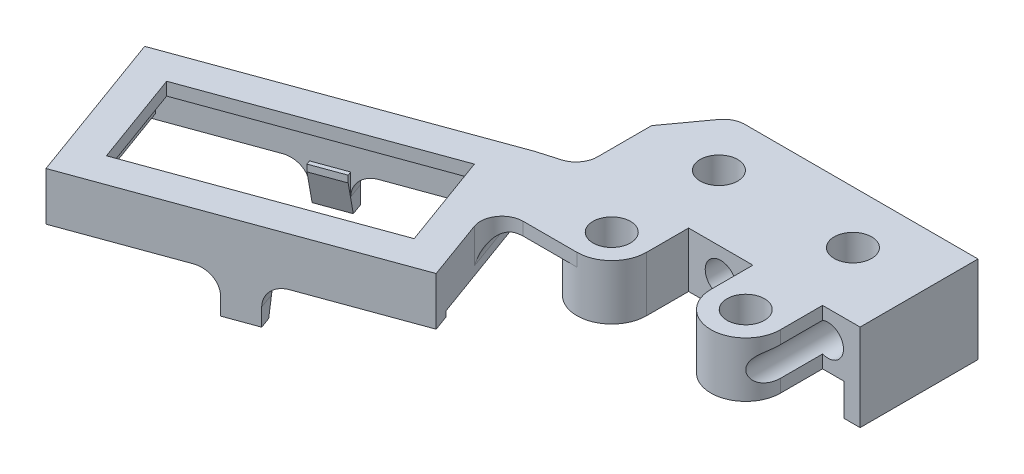
SolidWorks part; units mm, degrees
ref_plane "Front Plane" through (0, 0, 0) normal (0, 0, 1) x (1, 0, 0)
ref_plane "Top Plane" through (0, 0, 0) normal (0, 1, 0) x (1, 0, 0)
ref_plane "Right Plane" through (0, 0, 0) normal (1, 0, 0) x (0, 0, -1)
sketch "Sketch1" plane through (0, 0, 0) normal (0, 1, 0) x (1, 0, 0)
  line L5 (0, 0) -> (16.0528, 0) construction
  line L6 (0, 0) -> (0, -25.9338) construction
  line L7 (-6.25, 5) -> (-6.25, -5) construction
  line L8 (-6.25, 0) -> (0, 0) construction
  line L10 (-13, 9.92) -> (13, 9.92)
  line L11 (-13, 9.92) -> (-13, -9.92)
  line L12 (-13, -9.92) -> (13, -9.92)
  line L13 (13, 9.92) -> (13, -9.92)
  line L14 (-13, 9.92) -> (13, -9.92) construction
  line L15 (-13, -9.92) -> (13, 9.92) construction
  circle A7 centre (-6.25, 5) radius 1.75
  circle A8 centre (-6.25, -5) radius 1.75
  circle A9 centre (6.25, -5) radius 1.75
  circle A10 centre (6.25, 5) radius 1.75
  dimension "D3" = 3.5
  dimension "D4" = 12.5
  dimension "D5" = 10
  dimension "D7" = 26
  dimension "D8" = 4.92
extrude "Boss-Extrude1" add sketch "Sketch1" along normal blind 5.13 contours L13 L10 L11 L12 A9 A8 A7 A10
sketch "Sketch2" plane through (0, 0, 9.92) normal (0, 0, 1) x (1, 0, 0)
  line L0 (-13, 2.565) -> (13, 2.565) construction
  line L1 (-13, 5.13) -> (-13, 0) construction
  line L2 (13, 5.13) -> (13, 0) construction
  line L3 (0, 0) -> (0, 5.13) construction
  line L4 (-13, 5.13) -> (13, 5.13) construction
  circle A0 centre (0, 2.565) radius 1.45
  circle A1 centre (-10, 2.565) radius 1.45
  circle A2 centre (10, 2.565) radius 1.45
  dimension "D1" = 2.9
  dimension "D2" = 10
extrude "Cut-Extrude1" cut sketch "Sketch2" against normal up to next
sketch "Sketch3" plane through (0, 0, 0) normal (0, -1, 0) x (1, 0, 0)
  line L6 (-11.035, -9.92) -> (11.035, -9.92)
  line L7 (0, -9.92) -> (0, 3.71) construction
  line L8 (-13, -9.92) -> (13, -9.92) construction
  line L9 (-11.63, 3.71) -> (11.63, 3.71)
  line L10 (0, 3.71) -> (0, -9.92) construction
  line L11 (11.035, -9.92) -> (11.63, 3.71)
  line L12 (-11.035, -9.92) -> (-11.63, 3.71)
  line L13 (-10.92, 6.04) -> (10.92, 6.04)
  line L14 (0, 6.04) -> (0, -9.92) construction
  line L15 (-7.625, 12.72) -> (7.625, 12.72)
  line L16 (0, 12.72) -> (0, -9.92) construction
  line L17 (-7.625, 12.72) -> (-10.92, 6.04)
  line L18 (10.92, 6.04) -> (7.625, 12.72)
  line L19 (-9.0061, 9.92) -> (9.0061, 9.92)
  line L20 (-13, 9.92) -> (13, 9.92) construction
  line L22 (-13, 9.92) -> (13, 9.92)
  line L23 (-13, 9.92) -> (-13, -9.92)
  line L24 (-13, -9.92) -> (13, -9.92)
  line L25 (13, 9.92) -> (13, -9.92)
  spline S0 degree 2 poles (-11.63, 3.71) (-10.5122, 4.4663) (-10.92, 6.04) knots 0 0 0 1 1 1
  spline S1 degree 2 poles (11.63, 3.71) (10.5122, 4.4663) (10.92, 6.04) knots 0 0 0 1 1 1
  line M4 (13, -9.92) -> (13, 9.92)
  line M5 (13, 9.92) -> (-13, 9.92)
  line M6 (-13, 9.92) -> (-13, -9.92)
  line M7 (-13, -9.92) -> (13, -9.92)
  dimension "D8" = 22.07
  dimension "D9" = 23.26
  dimension "D11" = 13.63
  dimension "D12" = 21.84
  dimension "D14" = 2.33
  dimension "D15" = 15.25
  dimension "D17" = 6.68
extrude "Boss-Extrude2" add sketch "Sketch3" along normal blind 3 contours L12 S0 L17 M5 M6 M7 | S1 L11 L18 M7 M4 M5
sketch "Sketch4" plane through (0, -3, 0) normal (0, -1, 0) x (1, 0, 0)
  line L0 (-13, 1.08) -> (13, 1.08)
  line L1 (-13, 9.92) -> (-13, -9.92) construction
  line L2 (13, -9.92) -> (13, 9.92) construction
  line L3 (-9.5, 5) -> (-9.5, 1.08)
  line L4 (-11.035, -9.92) -> (11.035, -9.92) construction
  line L5 (-3, 5) -> (-3, 1.08)
  line L6 (3, 5) -> (3, 1.08)
  line L7 (9.5, 5) -> (9.5, 1.08)
  line L8 (-13, 1.08) -> (-13, 9.92)
  line L9 (-13, 9.92) -> (13, 9.92)
  line L10 (13, 9.92) -> (13, 1.08)
  circle A0 centre (-6.25, 5) radius 3.25
  circle A1 centre (-6.25, 5) radius 1.75 construction
  circle A2 centre (6.25, 5) radius 3.25
  spline M1 degree 2 poles (10.92, 6.04) (10.5122, 4.4663) (11.63, 3.71) knots 0 0 0 1 1 1
  line M2 (11.63, 3.71) -> (11.035, -9.92)
  line M4 (13, -9.92) -> (13, 9.92)
  line M5 (13, 9.92) -> (9.0061, 9.92)
  line M6 (9.0061, 9.92) -> (10.92, 6.04)
  dimension "D1" = 11
  dimension "D2" = 1.5
extrude "Cut-Extrude2" cut sketch "Sketch4" against normal up to next contours A2 L7 L0 L9 L8 L3 A0 L5 L6 M2 M1 M6 | L0 M2 M4 M5 M6 M1
sketch "Sketch5" plane through (0, 5.13, 0) normal (0, 1, 0) x (1, 0, 0)
  line L0 (-18.8665, -2.6039) -> (-10.3647, 9.0978) construction
  line L1 (-18.8665, -2.6039) -> (-10.3647, 9.0978)
  line L2 (-8.7467, 9.9222) -> (-13, 9.92)
  line L3 (-13, 9.92) -> (-13, 5.4706)
  line L4 (-13, 9.92) -> (-13, -1.08) construction
  arc A0 (-8.7467, 9.9222) -> (-10.3647, 9.0978) centre (-8.7467, 7.9222) ccw construction
  arc A1 (-8.7467, 9.9222) -> (-10.3647, 9.0978) centre (-8.7467, 7.9222) ccw
  line M3 (13, 9.92) -> (-13, 9.92)
  line M4 (-13, 9.92) -> (-13, -1.08)
extrude "Cut-Extrude3" cut sketch "Sketch5" against normal up to next contours A1 L1 M3 M4
sketch "Sketch6" plane through (0, 5.13, 0) normal (0, -1, 0) x (1, 0, 0)
  line L0 (-37.7857, 26.2448) -> (-11.0984, 16.5315)
  line L1 (-41.1302, 12.6701) -> (-17.262, 3.9828)
  line L2 (-41.1302, 12.6701) -> (-36.8892, 24.3223)
  line L3 (-36.8892, 24.3223) -> (-13.021, 15.6349)
  line L4 (-17.262, 3.9828) -> (-13.021, 15.6349)
  line L5 (-41.1302, 12.6701) -> (-13.021, 15.6349) construction
  line L6 (-36.8892, 24.3223) -> (-17.262, 3.9828) construction
  line L7 (-16.3655, 2.0602) -> (-11.0984, 16.5315)
  line L8 (-43.0528, 11.7736) -> (-16.3655, 2.0602)
  line L9 (-43.0528, 11.7736) -> (-37.7857, 26.2448)
  line L10 (-6.25, 8.25) -> (-14.1126, 8.25)
  line L11 (-13, 1.08) -> (-32.2548, 1.08) construction
  line L12 (-13, 1.08) -> (-46.0395, 13.1054) construction
  line L14 (-9.5, 5) -> (-9.5, 1.08) construction
  line L15 (-9.5, 5) -> (-9.5, 1.08)
  line L16 (-9.5, 1.08) -> (-13, 1.08)
  line L17 (-13, 1.08) -> (-16.3655, 2.0602)
  arc A0 (-3, 5) -> (-9.5, 5) centre (-6.25, 5) ccw construction
  arc A1 (-3, 5) -> (-9.5, 5) centre (-6.25, 5) ccw
  point P0 (-27.0756, 14.1525)
  dimension "D1" = 12.4
  dimension "D2" = 25.4
  dimension "D4" = 1.27
  dimension "D5" = 20
  dimension "D6" = 10
  dimension "D3" = 1.5
extrude "Boss-Extrude3" add sketch "Sketch6" along normal blind 1.2
sketch "Sketch9" plane through (0, 3.93, 0) normal (0, -1, 0) x (1, 0, 0)
  line L0 (-43.0528, 11.7736) -> (-37.7857, 26.2448)
  line L1 (-37.7857, 26.2448) -> (-11.0984, 16.5315)
  line L2 (-11.0984, 16.5315) -> (-16.3655, 2.0602)
  line L3 (-14.1126, 8.25) -> (-11.0984, 16.5315) construction
  line L4 (-43.0528, 11.7736) -> (-16.3655, 2.0602)
  line L5 (-43.0528, 11.7736) -> (-16.3655, 2.0602) construction
  line L6 (-41.1302, 12.6701) -> (-17.262, 3.9828)
  line L7 (-13.021, 15.6349) -> (-17.262, 3.9828)
  line L8 (-36.8892, 24.3223) -> (-13.021, 15.6349)
  line L9 (-41.1302, 12.6701) -> (-36.8892, 24.3223)
  dimension "D1" = 1.5
extrude "Boss-Extrude6" add sketch "Sketch9" along normal blind 3.3
sketch "Sketch10" plane through (0, 0.63, 0) normal (0, -1, 0) x (1, 0, 0)
  line L0 (-24.442, 21.3881) -> (-29.7092, 6.9169) construction
  line L1 (-11.0984, 16.5315) -> (-37.7857, 26.2448) construction
  line L2 (-43.0528, 11.7736) -> (-16.3655, 2.0602) construction
  line L3 (-31.1187, 7.4299) -> (-28.2996, 6.4038)
  line L4 (-31.1187, 7.4299) -> (-30.4689, 9.2153)
  line L5 (-28.2996, 6.4038) -> (-27.6498, 8.1893)
  line L6 (-30.4689, 9.2153) -> (-27.6498, 8.1893)
  line L7 (-29.0593, 8.7023) -> (-29.7092, 6.9169) construction
  line L8 (-41.1302, 12.6701) -> (-17.262, 3.9828) construction
  line L9 (-40.4192, 19.0092) -> (-13.732, 9.2958) construction
  line L10 (-37.7857, 26.2448) -> (-43.0528, 11.7736) construction
  line L11 (-16.3655, 2.0602) -> (-11.0984, 16.5315) construction
  line L12 (-25.8516, 21.9012) -> (-23.0325, 20.8751)
  line L13 (-25.8516, 21.9012) -> (-26.5014, 20.1158)
  line L14 (-26.5014, 20.1158) -> (-23.6823, 19.0897)
  line L15 (-23.0325, 20.8751) -> (-23.6823, 19.0897)
  dimension "D1" = 3
  dimension "D2" = 0.4
extrude "Boss-Extrude7" add sketch "Sketch10" along normal blind 0.8
sketch "Sketch11" plane through (0, 0.63, 0) normal (0, -1, 0) x (1, 0, 0)
  line L0 (-17.262, 3.9828) -> (-13.021, 15.6349)
  line L1 (-13.021, 15.6349) -> (-11.6114, 15.1219)
  line L2 (-16.3655, 2.0602) -> (-11.0984, 16.5315) construction
  line L3 (-11.6114, 15.1219) -> (-15.8525, 3.4697)
  line L4 (-15.8525, 3.4697) -> (-17.262, 3.9828)
  line L5 (-36.8892, 24.3223) -> (-41.1302, 12.6701)
  line L6 (-41.1302, 12.6701) -> (-42.5398, 13.1831)
  line L7 (-37.7857, 26.2448) -> (-43.0528, 11.7736) construction
  line L8 (-42.5398, 13.1831) -> (-38.2987, 24.8353)
  line L9 (-38.2987, 24.8353) -> (-36.8892, 24.3223)
extrude "Cut-Extrude4" cut sketch "Sketch11" against normal blind 0.5
sketch "Sketch12" plane through (0, 3.93, 0) normal (0, -1, 0) x (1, 0, 0)
  line L0 (-35.9927, 22.3997) -> (-39.2076, 13.5666)
  line L1 (-39.2076, 13.5666) -> (-18.1585, 5.9053)
  line L2 (-18.1585, 5.9053) -> (-14.9435, 14.7384)
  line L3 (-14.9435, 14.7384) -> (-35.9927, 22.3997)
  line L4 (-13.021, 15.6349) -> (-36.8892, 24.3223)
  line L5 (-36.8892, 24.3223) -> (-41.1302, 12.6701)
  line L6 (-41.1302, 12.6701) -> (-17.262, 3.9828)
  line L7 (-17.262, 3.9828) -> (-13.021, 15.6349)
  line L8 (-13.021, 15.6349) -> (-36.8892, 24.3223)
  line L9 (-36.8892, 24.3223) -> (-41.1302, 12.6701)
  line L10 (-41.1302, 12.6701) -> (-17.262, 3.9828)
  line L11 (-17.262, 3.9828) -> (-13.021, 15.6349)
  dimension "D1" = 0
  dimension "D2" = 1.5
extrude "Cut-Extrude5" cut sketch "Sketch12" against normal up to next contours L2 L3 L0 L1
sketch "Sketch13" plane through (0, -0.17, 0) normal (0, -1, 0) x (1, 0, 0)
  line L6 (-30.4689, 9.2153) -> (-31.1187, 7.4299)
  line L8 (-31.1187, 7.4299) -> (-28.2996, 6.4038)
  line L10 (-28.2996, 6.4038) -> (-27.6498, 8.1893)
  line L11 (-27.6498, 8.1893) -> (-30.4689, 9.2153)
  line L12 (-30.4689, 9.2153) -> (-31.1187, 7.4299)
  line L14 (-31.1187, 7.4299) -> (-28.2996, 6.4038)
  line L16 (-28.2996, 6.4038) -> (-27.6498, 8.1893)
  line L17 (-27.6498, 8.1893) -> (-30.4689, 9.2153)
  line L19 (-25.8516, 21.9012) -> (-26.5014, 20.1158)
  line L20 (-26.5014, 20.1158) -> (-23.6823, 19.0897)
  line L21 (-23.6823, 19.0897) -> (-23.0325, 20.8751)
  line L23 (-23.0325, 20.8751) -> (-25.8516, 21.9012)
  line L25 (-25.8516, 21.9012) -> (-26.5014, 20.1158)
  line L26 (-26.5014, 20.1158) -> (-23.6823, 19.0897)
  line L27 (-23.6823, 19.0897) -> (-23.0325, 20.8751)
  line L29 (-23.0325, 20.8751) -> (-25.8516, 21.9012)
  dimension "D1" = 0
  dimension "D2" = 0
extrude "Boss-Extrude8" add sketch "Sketch13" along normal blind 2.83
fillet "Fillet1" radius 2 7 edges at (-26.1081, 0.63, 21.1964) (-23.289, 0.63, 20.1703) (-13, 4.53, 1.08) (-14.1126, 4.53, 8.25) (-15.2391, 3.93, 5.1551)
chamfer "Chamfer1" distance 3 angle 15 2 edges at (-25.0919, -3, 19.6027) (-29.0593, -3, 8.7023)
